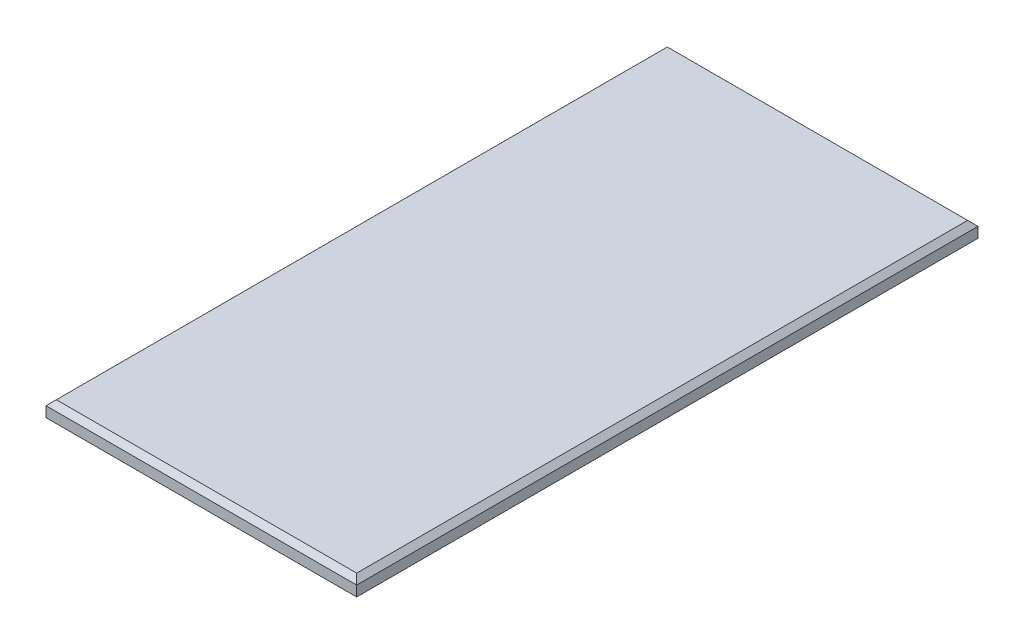
SolidWorks part; units mm, degrees
material "Maple"
ref_plane "Front Plane" through (0, 0, 0) normal (0, 0, 1) x (1, 0, 0)
ref_plane "Top Plane" through (0, 0, 0) normal (0, 1, 0) x (1, 0, 0)
ref_plane "Right Plane" through (0, 0, 0) normal (1, 0, 0) x (0, 0, -1)
sketch "Sketch1" plane through (0, 0, 0) normal (0, 1, 0) x (1, 0, 0)
  line L1 (-150, -300) -> (150, -300)
  line L2 (-150, -300) -> (-150, 300)
  line L3 (-150, 300) -> (150, 300)
  line L4 (150, -300) -> (150, 300)
  line L5 (-150, -300) -> (150, 300) construction
  line L6 (-150, 300) -> (150, -300) construction
  point P0 (0, 0)
  dimension "D1" = 300
  dimension "D2" = 600
extrude "Boss-Extrude1" add sketch "Sketch1" along normal blind 15 contours L2 L3 L4 L1
chamfer "Chamfer1" distance 5 angle 45 4 edges at (0, 15, 300) (-150, 15, 0) (0, 15, -300) (150, 15, 0)
